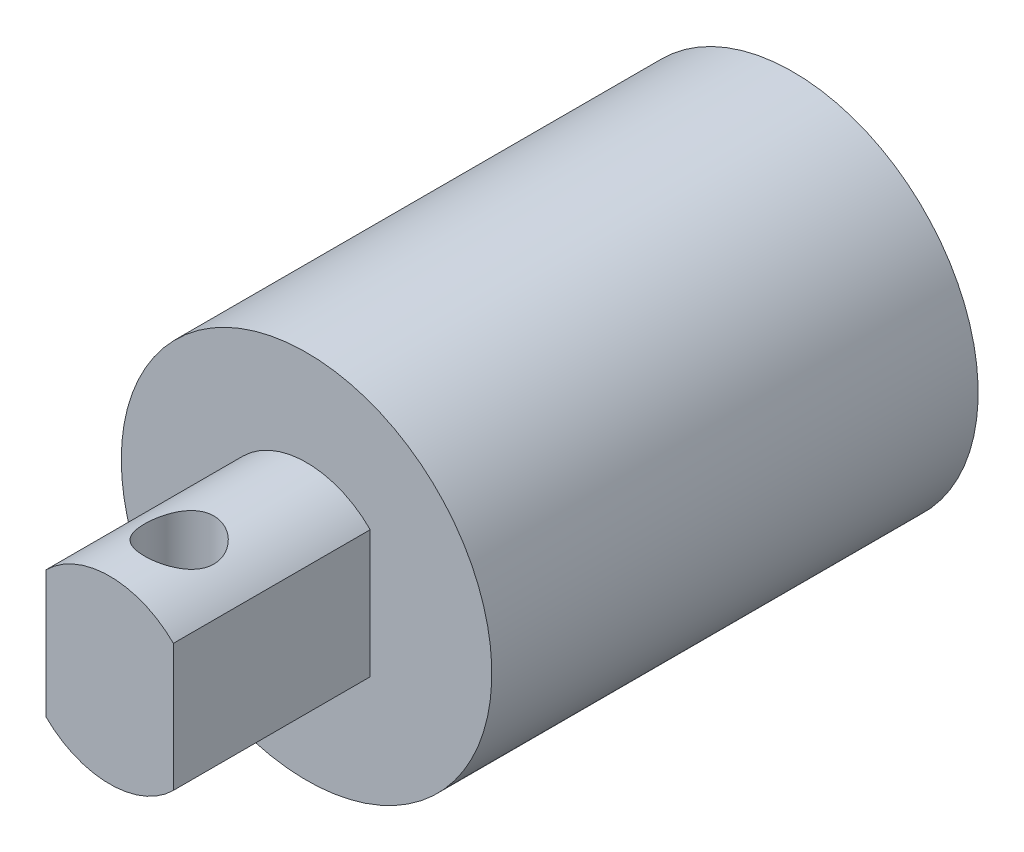
SolidWorks part; units mm, degrees
ref_plane "Front Plane" through (0, 0, 0) normal (0, 0, 1) x (1, 0, 0)
ref_plane "Top Plane" through (0, 0, 0) normal (0, 1, 0) x (1, 0, 0)
ref_plane "Right Plane" through (0, 0, 0) normal (1, 0, 0) x (0, 0, -1)
sketch "Sketch1" plane through (0, 0, 0) normal (0, 0, 1) x (1, 0, 0)
  circle A0 centre (0, 0) radius 8
  dimension "D1" = 16
extrude "Boss-Extrude1" add sketch "Sketch1" along normal blind 21
sketch "Sketch2" plane through (0, 0, 0) normal (0, 0, -1) x (-1, 0, 0)
  line L1 (-1.25, 3) -> (1.25, 3)
  line L2 (-1.25, 3) -> (-1.25, -6)
  line L3 (-1.25, -6) -> (1.25, -6)
  line L4 (1.25, 3) -> (1.25, -6)
  dimension "D1" = 3
  dimension "D2" = 6
  dimension "D3" = 2.5
  dimension "D4" = 1.25
extrude "Cut-Extrude1" cut sketch "Sketch2" against normal blind 10
sketch "Sketch3" plane through (0, 0, 0) normal (0, 0, -1) x (-1, 0, 0)
  circle A0 centre (0, 0) radius 2
  dimension "D1" = 4
extrude "Cut-Extrude2" cut sketch "Sketch3" against normal blind 2
sketch "Sketch4" plane through (0, 0, 21) normal (0, 0, 1) x (1, 0, 0)
  line L1 (-2.75, 2.75) -> (-2.75, -2.75)
  line L2 (2.75, 2.75) -> (2.75, -2.75)
  line L3 (-2.75, 2.75) -> (2.75, -2.75) construction
  line L4 (-2.75, -2.75) -> (2.75, 2.75) construction
  arc A0 (2.75, 2.75) -> (-2.75, 2.75) centre (0, 0) ccw
  arc A1 (-2.75, -2.75) -> (2.75, -2.75) centre (0, 0) ccw
  point P0 (0, 0)
  dimension "D1" = 5.5
  dimension "D2" = 5.5
extrude "Boss-Extrude2" add sketch "Sketch4" along normal blind 8.5
sketch "Sketch5" plane through (0, 0, 0) normal (0, 1, 0) x (1, 0, 0)
  line L0 (-2.75, -21) -> (2.75, -21) construction
  line L1 (0, 0) -> (0, -43.3303) construction
  circle A0 centre (0, -26.5) radius 1.5
  dimension "D1" = 3
  dimension "D2" = 5.5
extrude "Cut-Extrude3" cut sketch "Sketch5" against normal mid plane 8.5
